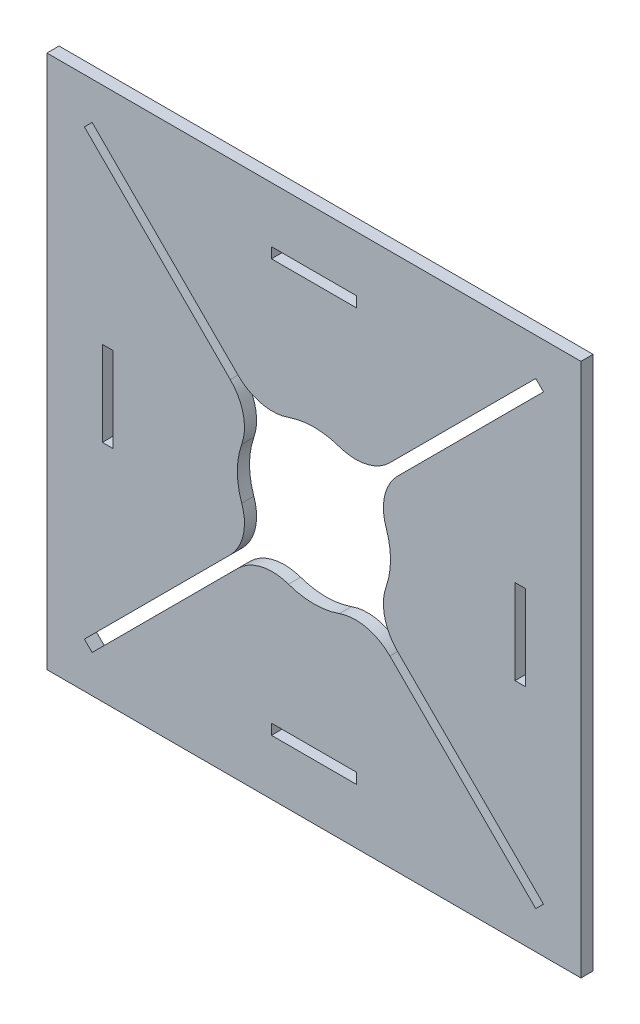
SolidWorks part; units mm, degrees
ref_plane "Front Plane" through (0, 0, 0) normal (0, 0, 1) x (1, 0, 0)
ref_plane "Top Plane" through (0, 0, 0) normal (0, 1, 0) x (1, 0, 0)
ref_plane "Right Plane" through (0, 0, 0) normal (1, 0, 0) x (0, 0, -1)
sketch "Sketch2" plane through (0, 0, 0) normal (0, 0, 1) x (1, 0, 0)
  line L0 (-43.7796, 39.7385) -> (-120.0837, 116.0426)
  line L1 (-139.7, 139.7) -> (139.7, 139.7)
  line L2 (-139.7, 139.7) -> (-139.7, -139.7)
  line L3 (-139.7, -139.7) -> (139.7, -139.7)
  line L4 (139.7, 139.7) -> (139.7, -139.7)
  line L5 (-139.7, 139.7) -> (139.7, -139.7) construction
  line L6 (-139.7, -139.7) -> (139.7, 139.7) construction
  line L7 (-120.0837, 116.0426) -> (-116.0426, 120.0837)
  line L8 (-39.7385, 43.7796) -> (-116.0426, 120.0837)
  line L9 (43.7796, 39.7385) -> (120.0837, 116.0426)
  line L10 (39.7385, 43.7796) -> (116.0426, 120.0837)
  line L11 (116.0426, 120.0837) -> (120.0837, 116.0426)
  line L12 (39.7385, -43.7796) -> (116.0426, -120.0837)
  line L13 (43.7796, -39.7385) -> (120.0837, -116.0426)
  line L14 (120.0837, -116.0426) -> (116.0426, -120.0837)
  line L15 (-43.7796, -39.7385) -> (-120.0837, -116.0426)
  line L16 (-39.7385, -43.7796) -> (-116.0426, -120.0837)
  line L17 (-116.0426, -120.0837) -> (-120.0837, -116.0426)
  line L18 (0, 0) -> (-13.3287, 37.7866) construction
  line L19 (0, -139.7) -> (0, 0) construction
  line L20 (-22.225, -105.1941) -> (22.225, -105.1941)
  line L21 (-22.225, -105.1941) -> (-22.225, -110.7059)
  line L22 (-22.225, -110.7059) -> (22.225, -110.7059)
  line L23 (22.225, -105.1941) -> (22.225, -110.7059)
  line L24 (-22.225, -105.1941) -> (22.225, -110.7059) construction
  line L25 (-22.225, -110.7059) -> (22.225, -105.1941) construction
  line L26 (-110.7059, 22.225) -> (-110.7059, -22.225)
  line L27 (-105.1941, 22.225) -> (-105.1941, -22.225)
  line L28 (-105.1941, -22.225) -> (-110.7059, -22.225)
  line L29 (-105.1941, 22.225) -> (-110.7059, 22.225)
  line L30 (22.225, 110.7059) -> (-22.225, 110.7059)
  line L31 (22.225, 105.1941) -> (-22.225, 105.1941)
  line L32 (-22.225, 105.1941) -> (-22.225, 110.7059)
  line L33 (22.225, 105.1941) -> (22.225, 110.7059)
  line L34 (110.7059, -22.225) -> (110.7059, 22.225)
  line L35 (105.1941, -22.225) -> (105.1941, 22.225)
  line L36 (105.1941, 22.225) -> (110.7059, 22.225)
  line L37 (105.1941, -22.225) -> (110.7059, -22.225)
  arc A0 (-37.7866, 13.3287) -> (-37.7866, -13.3287) centre (0, 0) ccw
  arc A1 (-39.7385, 43.7796) -> (-13.3287, 37.7866) centre (-21.778, 61.7401) ccw
  arc A2 (-43.7796, 39.7385) -> (-37.7866, 13.3287) centre (-61.7401, 21.778) cw
  arc A3 (43.7796, 39.7385) -> (37.7866, 13.3287) centre (61.7401, 21.778) ccw
  arc A4 (39.7385, 43.7796) -> (13.3287, 37.7866) centre (21.778, 61.7401) cw
  arc A5 (39.7385, -43.7796) -> (13.3287, -37.7866) centre (21.778, -61.7401) ccw
  arc A6 (43.7796, -39.7385) -> (37.7866, -13.3287) centre (61.7401, -21.778) cw
  arc A7 (-43.7796, -39.7385) -> (-37.7866, -13.3287) centre (-61.7401, -21.778) ccw
  arc A8 (-39.7385, -43.7796) -> (-13.3287, -37.7866) centre (-21.778, -61.7401) cw
  arc A9 (-13.3287, -37.7866) -> (13.3287, -37.7866) centre (0, 0) ccw
  arc A10 (37.7866, -13.3287) -> (37.7866, 13.3287) centre (0, 0) ccw
  arc A11 (13.3287, 37.7866) -> (-13.3287, 37.7866) centre (0, 0) ccw
  point P0 (0, 0)
  point P12 (-118.0631, 118.0631)
  point P14 (-26.24, 30.2811)
  point P17 (-30.2811, 26.24)
  point P18 (0, -107.95)
  point P50 (0, 0)
  point P51 (0, 0)
  point P52 (0, 0)
  point P65 (0, 0)
  point P66 (0, 0)
  dimension "D3" = 5.5118
  dimension "D6" = 25.4
  dimension "D1" = 279.4
  dimension "D2" = 279.4
  dimension "D4" = 127
  dimension "D5" = 5.715
  dimension "D8" = 40.0685
  dimension "D9" = 44.45
  dimension "D10" = 31.75
  dimension "D7" = 4
  dimension "D11" = 4
extrude "Boss-Extrude1" add sketch "Sketch2" along normal blind 6.35
